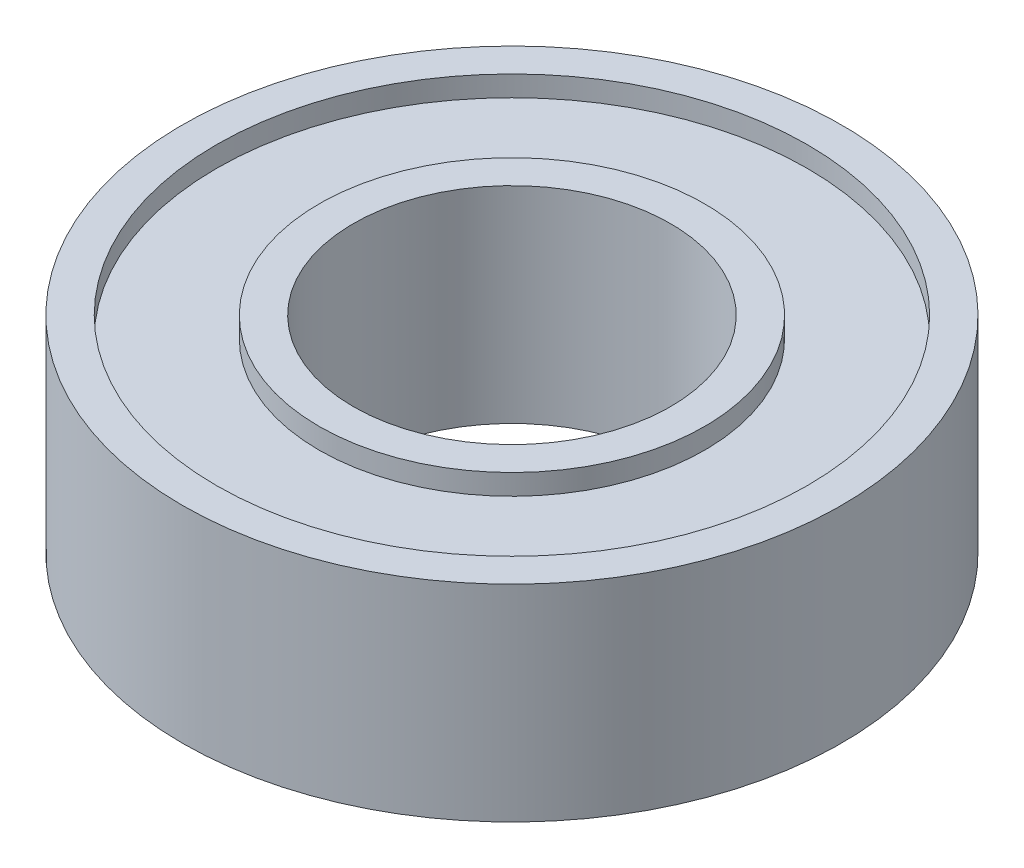
SolidWorks part; units mm, degrees
ref_plane "Спереди" through (0, 0, 0) normal (0, 0, 1) x (1, 0, 0)
ref_plane "Сверху" through (0, 0, 0) normal (0, 1, 0) x (1, 0, 0)
ref_plane "Справа" through (0, 0, 0) normal (1, 0, 0) x (0, 0, -1)
sketch "Эскиз1" plane through (0, 0, 0) normal (0, 1, 0) x (1, 0, 0)
  circle A0 centre (0, 0) radius 8
  circle A1 centre (0, 0) radius 3.85
  dimension "D1" = 16
  dimension "D2" = 7.7
extrude "Бобышка-Вытянуть1" add sketch "Эскиз1" along normal mid plane 5
sketch "Эскиз2" plane through (0, 2.5, 0) normal (0, 1, 0) x (1, 0, 0)
  circle A0 centre (0, 0) radius 4.68
  circle A1 centre (0, 0) radius 7.17
  circle A2 centre (0, 0) radius 3.85 construction
  circle A3 centre (0, 0) radius 8 construction
  dimension "D1" = 0.83
  dimension "D2" = 0.83
extrude "Вырез-Вытянуть1" cut sketch "Эскиз2" against normal blind 0.5
mirror "Зеркальное отражение1" about plane through (0, 0, 0) normal (0, 1, 0) of "Вырез-Вытянуть1"
equation "\"print_offset\"= 0.5"
equation "\"radial_bearing_d1\"= 7.7"
equation "\"radial_bearing_d2\"= 16"
equation "\"radial_bearing_h\"= 5"
equation "\"shaft_d\"= 6"
equation "\"shaft_h\" = 60"
equation "\"central_hole_d\"= 20"
equation "\"sitting_screws_d\"= 34"
equation "\"screw_d\"= 2"
equation "\"screw_hh_d\"= 3.4"
equation "\"screw_h\"= 8"
equation "\"screw_hh_h\"= 2"
equation "\"motor_screw_d\"= 3"
equation "\"motor_screw_hh_d\"= 5.6"
equation "\"motor_screw_h\" = 20"
equation "\"motor_screw_hh_h\"= 2"
equation "\"motor_nut_d\"= 5.4"
equation "\"motor_nut_h\"= 2.8"
equation "\"D1@Эскиз1\"=\"radial_bearing_d2\""
equation "\"D2@Эскиз1\"=\"radial_bearing_d1\""
equation "\"D1@Бобышка-Вытянуть1\"=\"radial_bearing_h\""
equation "\"D1@Эскиз2\"=(\"radial_bearing_d2\"-\"radial_bearing_d1\")*0.1"
equation "\"D2@Эскиз2\"=\"D1@Эскиз2\""
equation "\"D1@Вырез-Вытянуть1\"=\"radial_bearing_h\"*0.1"
